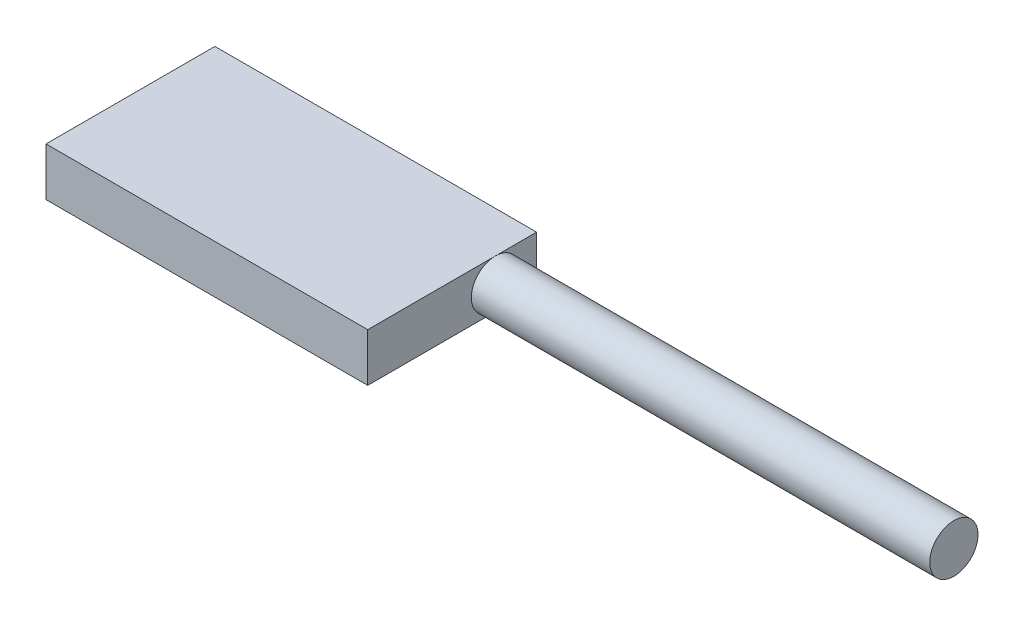
SolidWorks part; units mm, degrees
ref_plane "Front Plane" through (0, 0, 0) normal (0, 0, 1) x (1, 0, 0)
ref_plane "Top Plane" through (0, 0, 0) normal (0, 1, 0) x (1, 0, 0)
ref_plane "Right Plane" through (0, 0, 0) normal (1, 0, 0) x (0, 0, -1)
sketch "Sketch1" plane through (0, 0, 0) normal (0, 1, 0) x (1, 0, 0)
  line L1 (-20, 10.5) -> (20, 10.5)
  line L2 (-20, 10.5) -> (-20, -10.5)
  line L3 (-20, -10.5) -> (20, -10.5)
  line L4 (20, 10.5) -> (20, -10.5)
  line L5 (-20, 10.5) -> (20, -10.5) construction
  line L6 (-20, -10.5) -> (20, 10.5) construction
  point P0 (0, 0)
  dimension "D1" = 40
  dimension "D2" = 21
extrude "Boss-Extrude1" add sketch "Sketch1" along normal blind 6
sketch "Sketch3" plane through (20, 0, 0) normal (1, 0, 0) x (0, 0, -1)
  circle A0 centre (5.3799, 3) radius 3
  dimension "D1" = 6
extrude "Boss-Extrude2" add sketch "Sketch3" along normal blind 57
